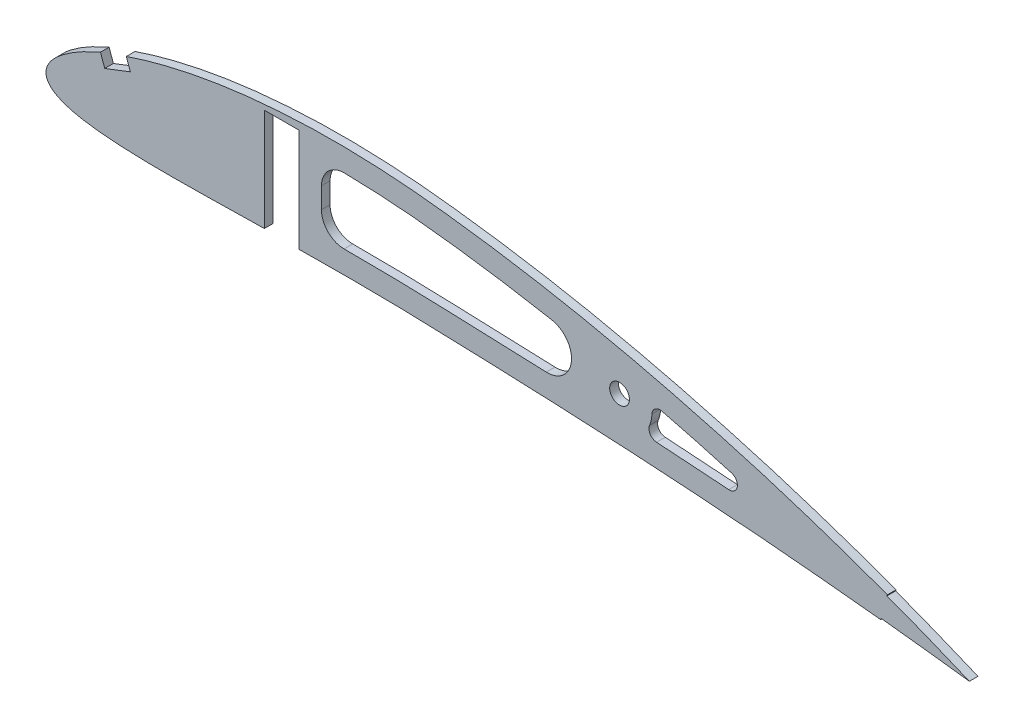
SolidWorks part; units mm, degrees
ref_plane "Front Plane" through (0, 0, 0) normal (0, 0, 1) x (1, 0, 0)
ref_plane "Top Plane" through (0, 0, 0) normal (0, 1, 0) x (1, 0, 0)
ref_plane "Right Plane" through (0, 0, 0) normal (1, 0, 0) x (0, 0, -1)
curve "ImportedCurve1"
curve "ImportedCurve2"
curve "ImportedCurve3"
curve "ImportedCurve4"
curve "ImportedCurve5"
curve "ImportedCurve6"
curve "ImportedCurve7"
curve "ImportedCurve8"
curve "ImportedCurve9"
curve "ImportedCurve10"
curve "ImportedCurve11"
curve "ImportedCurve12"
curve "ImportedCurve13"
curve "ImportedCurve14"
curve "ImportedCurve15"
curve "ImportedCurve16"
curve "ImportedCurve17"
curve "ImportedCurve18"
curve "ImportedCurve19"
curve "ImportedCurve20"
curve "ImportedCurve21"
curve "ImportedCurve22"
curve "ImportedCurve23"
curve "ImportedCurve24"
curve "ImportedCurve25"
curve "ImportedCurve26"
curve "ImportedCurve27"
sketch "Sketch2" plane through (0, 0, 0) normal (0, 0, 1) x (1, 0, 0)
  line L0 (2535.2748, 2780.8932) -> (2535.2748, 2740.5434) construction
  line L1 (2548.8638, 2780.8932) -> (2535.2748, 2780.8932) construction
  line L2 (2548.8638, 2780.8932) -> (2548.8638, 2740.7885) construction
  line L3 (2548.8638, 2740.7885) -> (2548.8703, 2740.2681) construction
  line L4 (2482.5221, 2767.5816) -> (2480.9335, 2772.0377) construction
  line L5 (2780.3662, 2737.8319) -> (2780.5425, 2738.3048) construction
  line L6 (2557.7538, 2766.3381) -> (2557.7538, 2758.1737) construction
  line L7 (2778.0193, 2729.0443) -> (2777.9678, 2728.5204) construction
  line L8 (2472.4468, 2763.6963) -> (2470.7661, 2768.4105) construction
  line L9 (2472.4468, 2763.6963) -> (2482.5221, 2767.5816) construction
  line L10 (2535.2748, 2780.8932) -> (2535.2748, 2740.5434)
  line L11 (2548.8638, 2780.8932) -> (2535.2748, 2780.8932)
  line L12 (2548.8638, 2780.8932) -> (2548.8638, 2740.7885)
  line L13 (2548.8638, 2740.7885) -> (2548.8703, 2740.2681)
  line L14 (2482.5221, 2767.5816) -> (2480.9335, 2772.0377)
  line L15 (2780.3662, 2737.8319) -> (2780.5425, 2738.3048)
  line L16 (2557.7538, 2766.3381) -> (2557.7538, 2758.1737)
  line L17 (2778.0193, 2729.0443) -> (2777.9678, 2728.5204)
  line L18 (2472.4468, 2763.6963) -> (2470.7661, 2768.4105)
  line L19 (2472.4468, 2763.6963) -> (2482.5221, 2767.5816)
  arc A0 (2566.7617, 2775.2273) -> (2557.7538, 2766.3381) centre (2566.6438, 2766.3381) ccw construction
  arc A1 (2646.2636, 2747.1034) -> (2648.4261, 2765.9833) centre (2646.6833, 2756.6191) ccw construction
  arc A2 (2718.0983, 2742.9488) -> (2719.2039, 2749.1678) centre (2718.3306, 2746.1152) ccw construction
  arc A3 (2686.9168, 2749.2705) -> (2689.6687, 2744.8901) centre (2689.8519, 2748.0598) ccw construction
  arc A4 (2691.8173, 2756.5185) -> (2687.8696, 2753.5795) centre (2691.0416, 2753.4397) ccw construction
  arc A5 (2557.7538, 2758.1737) -> (2566.6631, 2749.2837) centre (2566.6438, 2758.1737) ccw construction
  arc A6 (2686.9168, 2749.2705) -> (2687.8696, 2753.5795) centre (2675.1058, 2754.1421) ccw construction
  arc A7 (2671.2196, 2754.1421) -> (2678.992, 2754.1421) centre (2675.1058, 2754.1421) ccw construction
  arc A8 (2678.992, 2754.1421) -> (2671.2196, 2754.1421) centre (2675.1058, 2754.1421) ccw construction
  arc A9 (2566.7617, 2775.2273) -> (2557.7538, 2766.3381) centre (2566.6438, 2766.3381) ccw
  arc A10 (2646.2636, 2747.1034) -> (2648.4261, 2765.9833) centre (2646.6833, 2756.6191) ccw
  arc A11 (2718.0983, 2742.9488) -> (2719.2039, 2749.1678) centre (2718.3306, 2746.1152) ccw
  arc A12 (2686.9168, 2749.2705) -> (2689.6687, 2744.8901) centre (2689.8519, 2748.0598) ccw
  arc A13 (2691.8173, 2756.5185) -> (2687.8696, 2753.5795) centre (2691.0416, 2753.4397) ccw
  arc A14 (2557.7538, 2758.1737) -> (2566.6631, 2749.2837) centre (2566.6438, 2758.1737) ccw
  arc A15 (2686.9168, 2749.2705) -> (2687.8696, 2753.5795) centre (2675.1058, 2754.1421) ccw
  arc A16 (2671.2196, 2754.1421) -> (2678.992, 2754.1421) centre (2675.1058, 2754.1421) ccw
  arc A17 (2678.992, 2754.1421) -> (2671.2196, 2754.1421) centre (2675.1058, 2754.1421) ccw
  spline S0 degree 3 poles (4384.4323, 5266.1021) (2910.9243, 2624.3907) (2853.954, 2712.0921) (2771.0083, 2741.8063) (2768.1814, 2742.7975) (2759.6259, 2745.8482) (2753.8405, 2747.7555) (2742.2387, 2751.5185) (2736.4236, 2753.3673) (2724.7514, 2756.8564) (2718.8821, 2758.5163) (2708.1862, 2761.4752) (2703.3757, 2762.7592) (2693.6886, 2765.2072) (2688.8603, 2766.4493) (2679.1367, 2768.7098) (2674.2578, 2769.7817) (2664.5083, 2771.9262) (2659.6168, 2772.9274) (2649.829, 2774.789) (2644.9068, 2775.7085) (2635.0811, 2777.3896) (2630.1347, 2778.191) (2621.1638, 2779.5046) (2617.0759, 2780.0849) (2607.9501, 2781.2472) (2602.8464, 2781.8206) (2592.6809, 2782.8833) (2587.5833, 2783.2541) (2577.3759, 2783.8633) (2572.2642, 2784.0456) (2562.055, 2784.1771) (2556.9405, 2784.1314) (2546.7263, 2783.7503) (2541.6202, 2783.4533) (2522.3779, 2781.8658) (2508.2725, 2779.6653) (2320.4271, 2731.1029) (2188.8509, 2445.5723) (4416.5552, 529.9403) knots -8.174567 -8.174567 -8.174567 -8.174567 1.898612 1.898612 2.25157 2.25157 2.97238 2.97238 3.693189 3.693189 4.413999 4.413999 5.004035 5.004035 5.59407 5.59407 6.184105 6.184105 6.774141 6.774141 7.364176 7.364176 7.954212 7.954212 8.439681 8.439681 9.044668 9.044668 9.649655 9.649655 10.254642 10.254642 10.859629 10.859629 11.464616 11.464616 13.146197 13.146197 34.504055 34.504055 34.504055 34.504055 only from (2780.5425, 2738.3048) to (2480.9335, 2772.0377) construction
  spline S1 degree 3 poles (-185.9814, 2787.8047) (2948.6758, 2676.2823) (2862.0493, 2704.5268) (2805.162, 2728.1222) (2800.7468, 2729.91) (2791.811, 2733.5312) (2787.3909, 2735.2268) (2640.0751, 2789.8524) (2503.651, 2850.0947) (943.052, 390.1957) knots -6.327853 -6.327853 -6.327853 -6.327853 0.376825 0.376825 0.943228 0.943228 1.509632 1.509632 19.523491 19.523491 19.523491 19.523491 only from (2812.8112, 2724.9489) to (2780.3662, 2737.8319) construction
  spline S2 degree 3 poles (1731.4152, 5583.6671) (2108.673, 2748.4196) (2331.852, 2737.2501) (2556.9478, 2740.3769) (2562.0305, 2740.3786) (2567.1738, 2740.3938) (2572.378, 2740.4095) (2577.6546, 2740.3773) (2582.9782, 2740.2824) (2588.3501, 2740.2364) (2593.7796, 2740.0516) (2599.3074, 2739.8975) (2604.9087, 2739.7189) (2610.5722, 2739.5668) (2616.2572, 2739.3223) (2621.9699, 2739.1768) (2627.6798, 2738.946) (2633.4021, 2738.7339) (2639.1368, 2738.5299) (2644.8687, 2738.2654) (2650.5883, 2738.0131) (2656.2963, 2737.781) (2661.9877, 2737.4596) (2667.6718, 2737.256) (2673.3112, 2736.9034) (2678.9152, 2736.5953) (2684.4815, 2736.2758) (2690.0115, 2735.9734) (2695.4894, 2735.6279) (2700.9022, 2735.2394) (2706.2541, 2734.8684) (2711.544, 2734.4954) (2716.7484, 2734.1405) (2721.8762, 2733.7497) (2726.912, 2733.296) (2731.8817, 2732.9419) (2736.7578, 2732.5051) (2741.5391, 2732.1159) (2746.2156, 2731.6618) (2750.7708, 2731.2365) (2755.2146, 2730.814) (2759.5346, 2730.3954) (2763.7464, 2730.0087) (2767.8261, 2729.543) (2771.7933, 2729.189) (2830.2572, 2722.2922) (2891.0185, 2750.1032) (2630.399, -264.8508) knots -6.673608 -6.673608 -6.673608 -6.673608 19.516306 19.714059 19.914611 20.11662 20.32154 20.529276 20.739841 20.950405 21.163745 21.381461 21.603554 21.825647 22.050605 22.275616 22.500574 22.725533 22.95195 23.178326 23.403242 23.628157 23.85304 24.076496 24.299895 24.520375 24.739394 24.958414 25.174499 25.387659 25.599359 25.808139 26.013999 26.215484 26.415525 26.611171 26.803913 26.993735 27.177747 27.35884 27.534095 27.704971 27.871469 28.033634 28.189916 28.341868 34.986111 34.986111 34.986111 34.986111 only from (2548.8703, 2740.2681) to (2777.9678, 2728.5204) construction
  spline S3 degree 3 poles (1279.8362, 5276.8775) (2302.5068, 2663.4598) (2541.681, 2756.1071) (2787.9969, 2727.9102) (2794.5403, 2727.2012) (2903.4903, 2713.7931) (2979.9344, 2676.7139) (5271.3811, 4436.9092) knots 0.087148 0.087148 0.087148 0.087148 28.56999 28.56999 29.343341 29.343341 41.606171 41.606171 41.606171 41.606171 only from (2778.0193, 2729.0443) to (2812.8112, 2724.9489) construction
  spline S4 degree 3 poles (1096.4168, 5412.0407) (2934.863, 2563.7645) (2626.4941, 2836.7746) (2466.9137, 2766.72) (2463.4641, 2765.0446) (2457.8844, 2761.6159) (2455.6089, 2760.0224) (2451.9641, 2756.6756) (2450.4657, 2754.9477) (2449.2892, 2751.741) (2449.1568, 2750.4401) (2449.952, 2748.0643) (2450.8099, 2747.0151) (2452.68, 2745.5327) (2453.701, 2744.9752) (2455.7378, 2744.0361) (2456.8244, 2743.6654) (2460.2041, 2742.6077) (2462.5683, 2742.1477) (2467.3207, 2741.3721) (2469.7198, 2741.1063) (2476.9483, 2740.4649) (2481.785, 2740.2115) (2491.4695, 2739.9815) (2496.312, 2739.9702) (2511.0794, 2740.0542) (2520.9791, 2740.2846) (2734.0197, 2744.0833) (2938.7969, 2779.8609) (3138.7292, -160.7029) knots -6.087252 -6.087252 -6.087252 -6.087252 14.151211 14.151211 14.604184 14.604184 14.932416 14.932416 15.199765 15.199765 15.362932 15.362932 15.5261 15.5261 15.66286 15.66286 15.79962 15.79962 16.086125 16.086125 16.37263 16.37263 16.945639 16.945639 17.518648 17.518648 18.689255 18.689255 42.687215 42.687215 42.687215 42.687215 only from (2470.7661, 2768.4105) to (2535.2748, 2740.5434) construction
  spline S5 degree 3 poles (5488.3057, 3822.9496) (2475.7543, 2725.6654) (2586.733, 2751.416) (2699.0659, 2744.3068) (2704.6007, 2743.8946) (2831.726, 2734.9974) (2978.5478, 2741.4855) (4363.2595, 246.5938) knots 12.614051 12.614051 12.614051 12.614051 25.070609 25.070609 25.727122 25.727122 40.146551 40.146551 40.146551 40.146551 only from (2689.6687, 2744.8901) to (2718.0983, 2742.9488) construction
  spline S6 degree 3 poles (4593.2417, 513.9443) (3459.7127, 2114.0926) (3112.1592, 2694.5181) (2619.3252, 2770.8086) (2610.8711, 2771.9416) (2595.7157, 2773.6459) (2589.3146, 2774.2447) (2364.4075, 2787.5013) (2162.3899, 2626.9486) (2660.8909, -184.7765) knots -50.791509 -50.791509 -50.791509 -50.791509 7.794516 7.794516 8.825426 8.825426 9.617156 9.617156 36.077434 36.077434 36.077434 36.077434 only from (2648.4261, 2765.9833) to (2566.7617, 2775.2273) construction
  spline S7 degree 3 poles (151.4501, 4299.2846) (3072.4524, 2594.1514) (2854.8051, 2713.0974) (2547.5736, 2795.1827) (2314.1472, 2768.1328) (2826.4187, 5723.9904) knots -14.092475 -14.092475 -14.092475 -14.092475 4.675696 4.675696 24.218929 24.218929 24.218929 24.218929 only from (2719.2039, 2749.1678) to (2691.8173, 2756.5185) construction
  spline S8 degree 3 poles (-430.6592, 2625.1337) (2444.1933, 2750.6784) (2482.3775, 2749.0798) (2573.5871, 2749.3001) (2578.3279, 2749.2448) (2585.825, 2749.1426) (2589.0364, 2749.0998) (2595.1651, 2748.9088) (2598.1673, 2748.8234) (2604.2577, 2748.6367) (2607.2482, 2748.5585) (2612.8674, 2748.3699) (2615.291, 2748.262) (2620.1241, 2748.1107) (2622.6619, 2748.0389) (2627.6217, 2747.8499) (2630.0511, 2747.754) (2751.5571, 2743.2975) (2940.4921, 2721.2173) (-343.0487, 2998.1998) knots 10.015171 10.015171 10.015171 10.015171 20.190363 20.190363 20.729095 20.729095 21.088164 21.088164 21.447233 21.447233 21.806302 21.806302 22.096768 22.096768 22.387234 22.387234 22.677701 22.677701 36.790099 36.790099 36.790099 36.790099 only from (2566.6631, 2749.2837) to (2646.2636, 2747.1034) construction
  spline S9 degree 3 poles (2780.5425, 2738.3048) (2778.2975, 2739.142) (2776.066, 2739.9944) (2771.0083, 2741.8063) (2768.1814, 2742.7975) (2759.6259, 2745.8482) (2753.8405, 2747.7555) (2742.2387, 2751.5185) (2736.4236, 2753.3673) (2724.7514, 2756.8564) (2718.8821, 2758.5163) (2708.1862, 2761.4752) (2703.3757, 2762.7592) (2693.6886, 2765.2072) (2688.8603, 2766.4493) (2679.1367, 2768.7098) (2674.2578, 2769.7817) (2664.5083, 2771.9262) (2659.6168, 2772.9274) (2649.829, 2774.789) (2644.9068, 2775.7085) (2635.0811, 2777.3896) (2630.1347, 2778.191) (2621.1638, 2779.5046) (2617.0759, 2780.0849) (2607.9501, 2781.2472) (2602.8464, 2781.8206) (2592.6809, 2782.8833) (2587.5833, 2783.2541) (2577.3759, 2783.8633) (2572.2642, 2784.0456) (2562.055, 2784.1771) (2556.9405, 2784.1314) (2546.7263, 2783.7503) (2541.6202, 2783.4533) (2522.3779, 2781.8658) (2508.2725, 2779.6653) (2489.9757, 2774.9352) (2485.4186, 2773.5826) (2480.9335, 2772.0377) knots 1.615826 1.615826 1.615826 1.615826 1.898612 1.898612 2.25157 2.25157 2.97238 2.97238 3.693189 3.693189 4.413999 4.413999 5.004035 5.004035 5.59407 5.59407 6.184105 6.184105 6.774141 6.774141 7.364176 7.364176 7.954212 7.954212 8.439681 8.439681 9.044668 9.044668 9.649655 9.649655 10.254642 10.254642 10.859629 10.859629 11.464616 11.464616 13.146197 13.146197 13.708744 13.708744 13.708744 13.708744
  spline S10 degree 3 poles (2812.8112, 2724.9489) (2811.7427, 2725.3959) (2810.661, 2725.8414) (2805.162, 2728.1222) (2800.7468, 2729.91) (2791.811, 2733.5312) (2787.3909, 2735.2268) (2782.0553, 2737.2052) (2781.2108, 2737.5187) (2780.3662, 2737.8319) knots 0.240373 0.240373 0.240373 0.240373 0.376825 0.376825 0.943228 0.943228 1.509632 1.509632 1.616177 1.616177 1.616177 1.616177
  spline S11 degree 3 poles (2548.8703, 2740.2681) (2549.8808, 2740.2808) (2552.5653, 2740.316) (2556.9478, 2740.3769) (2562.0305, 2740.3786) (2567.1738, 2740.3938) (2572.378, 2740.4095) (2577.6546, 2740.3773) (2582.9782, 2740.2824) (2588.3501, 2740.2364) (2593.7796, 2740.0516) (2599.3074, 2739.8975) (2604.9087, 2739.7189) (2610.5722, 2739.5668) (2616.2572, 2739.3223) (2621.9699, 2739.1768) (2627.6798, 2738.946) (2633.4021, 2738.7339) (2639.1368, 2738.5299) (2644.8687, 2738.2654) (2650.5883, 2738.0131) (2656.2963, 2737.781) (2661.9877, 2737.4596) (2667.6718, 2737.256) (2673.3112, 2736.9034) (2678.9152, 2736.5953) (2684.4815, 2736.2758) (2690.0115, 2735.9734) (2695.4894, 2735.6279) (2700.9022, 2735.2394) (2706.2541, 2734.8684) (2711.544, 2734.4954) (2716.7484, 2734.1405) (2721.8762, 2733.7497) (2726.912, 2733.296) (2731.8817, 2732.9419) (2736.7578, 2732.5051) (2741.5391, 2732.1159) (2746.2156, 2731.6618) (2750.7708, 2731.2365) (2755.2146, 2730.814) (2759.5346, 2730.3954) (2763.7464, 2730.0087) (2767.8261, 2729.543) (2771.7933, 2729.189) (2775.1515, 2728.7928) (2777.2, 2728.5959) (2777.9678, 2728.5204) knots 19.396956 19.396956 19.396956 19.396956 19.516306 19.714059 19.914611 20.11662 20.32154 20.529276 20.739841 20.950405 21.163745 21.381461 21.603554 21.825647 22.050605 22.275616 22.500574 22.725533 22.95195 23.178326 23.403242 23.628157 23.85304 24.076496 24.299895 24.520375 24.739394 24.958414 25.174499 25.387659 25.599359 25.808139 26.013999 26.215484 26.415525 26.611171 26.803913 26.993735 27.177747 27.35884 27.534095 27.704971 27.871469 28.033634 28.189916 28.341868 28.432981 28.432981 28.432981 28.432981
  spline S12 degree 3 poles (2778.0193, 2729.0443) (2779.1748, 2728.9173) (2780.3303, 2728.7878) (2787.9969, 2727.9102) (2794.5403, 2727.2012) (2804.9356, 2725.9219) (2808.8293, 2725.402) (2812.8112, 2724.9489) knots 28.432747 28.432747 28.432747 28.432747 28.56999 28.56999 29.343341 29.343341 29.813814 29.813814 29.813814 29.813814
  spline S13 degree 3 poles (2470.7661, 2768.4105) (2470.6464, 2768.3584) (2470.5267, 2768.3061) (2466.9137, 2766.72) (2463.4641, 2765.0446) (2457.8844, 2761.6159) (2455.6089, 2760.0224) (2451.9641, 2756.6756) (2450.4657, 2754.9477) (2449.2892, 2751.741) (2449.1568, 2750.4401) (2449.952, 2748.0643) (2450.8099, 2747.0151) (2452.68, 2745.5327) (2453.701, 2744.9752) (2455.7378, 2744.0361) (2456.8244, 2743.6654) (2460.2041, 2742.6077) (2462.5683, 2742.1477) (2467.3207, 2741.3721) (2469.7198, 2741.1063) (2476.9483, 2740.4649) (2481.785, 2740.2115) (2491.4695, 2739.9815) (2496.312, 2739.9702) (2511.0794, 2740.0542) (2520.9791, 2740.2846) (2532.35, 2740.4873) (2533.8124, 2740.5151) (2535.2748, 2740.5434) knots 14.135709 14.135709 14.135709 14.135709 14.151211 14.151211 14.604184 14.604184 14.932416 14.932416 15.199765 15.199765 15.362932 15.362932 15.5261 15.5261 15.66286 15.66286 15.79962 15.79962 16.086125 16.086125 16.37263 16.37263 16.945639 16.945639 17.518648 17.518648 18.689255 18.689255 18.862005 18.862005 18.862005 18.862005
  spline S14 degree 3 poles (2689.6687, 2744.8901) (2690.9236, 2744.8176) (2692.183, 2744.7424) (2699.0659, 2744.3068) (2704.6007, 2743.8946) (2712.7745, 2743.3225) (2715.4243, 2743.145) (2718.0983, 2742.9488) knots 24.92366 24.92366 24.92366 24.92366 25.070609 25.070609 25.727122 25.727122 26.039952 26.039952 26.039952 26.039952
  spline S15 degree 3 poles (2648.4261, 2765.9833) (2641.5924, 2767.2552) (2634.7338, 2768.4234) (2619.3252, 2770.8086) (2610.8711, 2771.9416) (2595.7157, 2773.6459) (2589.3146, 2774.2447) (2577.4277, 2774.9453) (2572.0848, 2775.1567) (2566.7617, 2775.2273) knots 6.961493 6.961493 6.961493 6.961493 7.794516 7.794516 8.825426 8.825426 9.617156 9.617156 10.265753 10.265753 10.265753 10.265753
  spline S16 degree 3 poles (2719.2039, 2749.1678) (2714.2381, 2750.5884) (2709.2315, 2751.9914) (2700.185, 2754.4084) (2696.0201, 2755.4596) (2691.8173, 2756.5185) knots 4.06038 4.06038 4.06038 4.06038 4.675696 4.675696 5.188469 5.188469 5.188469 5.188469
  spline S17 degree 3 poles (2566.6631, 2749.2837) (2567.4398, 2749.2854) (2568.2183, 2749.2871) (2573.5871, 2749.3001) (2578.3279, 2749.2448) (2585.825, 2749.1426) (2589.0364, 2749.0998) (2595.1651, 2748.9088) (2598.1673, 2748.8234) (2604.2577, 2748.6367) (2607.2482, 2748.5585) (2612.8674, 2748.3699) (2615.291, 2748.262) (2620.1241, 2748.1107) (2622.6619, 2748.0389) (2627.6217, 2747.8499) (2630.0511, 2747.754) (2637.0527, 2747.4972) (2641.7061, 2747.3044) (2646.2636, 2747.1034) knots 20.098452 20.098452 20.098452 20.098452 20.190363 20.190363 20.729095 20.729095 21.088164 21.088164 21.447233 21.447233 21.806302 21.806302 22.096768 22.096768 22.387234 22.387234 22.677701 22.677701 23.217184 23.217184 23.217184 23.217184
extrude "Boss-Extrude1" add sketch "Sketch2" along normal blind 3.4036
